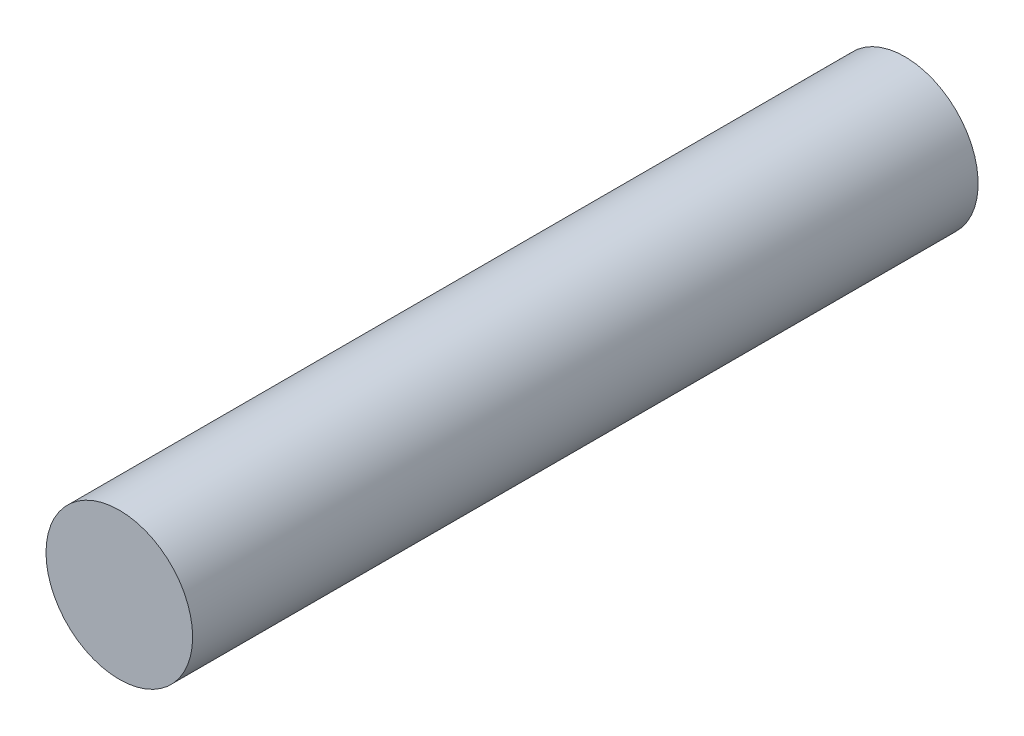
SolidWorks part; units mm, degrees
ref_plane "Front Plane" through (0, 0, 0) normal (0, 0, 1) x (1, 0, 0)
ref_plane "Top Plane" through (0, 0, 0) normal (0, 1, 0) x (1, 0, 0)
ref_plane "Right Plane" through (0, 0, 0) normal (1, 0, 0) x (0, 0, -1)
sketch "Sketch1" plane through (0, 0, 0) normal (0, 0, 1) x (1, 0, 0)
  circle A0 centre (0, 0) radius 7
  dimension "D1" = 14
extrude "Boss-Extrude1" add sketch "Sketch1" along normal blind 50
sketch "Sketch3" plane through (0, 0, 0) normal (0, 0, -1) x (-1, 0, 0)
  point P0 (0, 0)
sketch "Sketch5" plane through (0, 0, 0) normal (0, 0, -1) x (-1, 0, 0)
  circle A0 centre (0, 0) radius 7
  circle A1 centre (0, 0) radius 7 construction
extrude "Boss-Extrude2" add sketch "Sketch5" along normal blind 25
